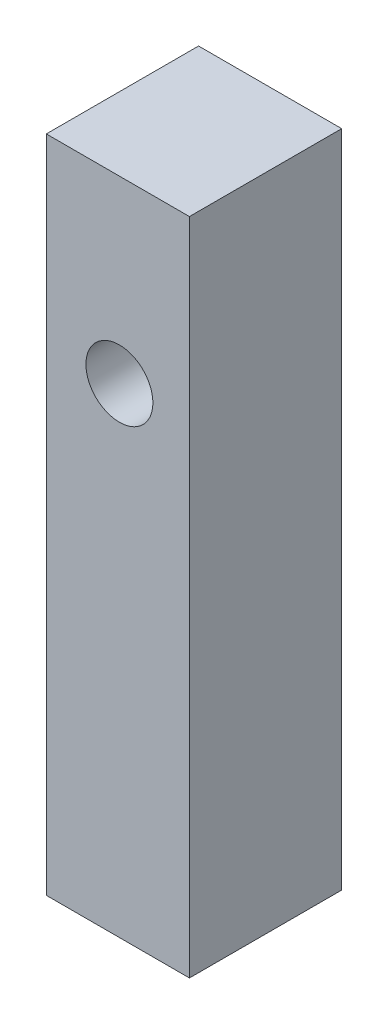
SolidWorks part; units mm, degrees
ref_plane "前视基准面" through (0, 0, 0) normal (0, 0, 1) x (1, 0, 0)
ref_plane "上视基准面" through (0, 0, 0) normal (0, 1, 0) x (1, 0, 0)
ref_plane "右视基准面" through (0, 0, 0) normal (1, 0, 0) x (0, 0, -1)
other "Configuration Table"
sketch "草图1" plane through (0, 0, 0) normal (0, 0, 1) x (1, 0, 0)
  line L5 (11.25, -15.755) -> (15.95, -15.755)
  line L6 (-23.0958, -15.755) -> (-18.4458, -15.755) construction
  line L7 (15.95, -5.9) -> (15.95, -0.65)
  line L8 (15.95, -0.65) -> (14.4099, -0.65)
  line L9 (14.4099, 0.65) -> (15.95, 0.65)
  line L10 (15.95, 0.65) -> (15.95, 5.9)
  line L11 (15.95, 5.9) -> (11.25, 5.9)
  line L12 (11.25, 5.9) -> (11.25, -5.9)
  line L13 (11.25, -5.9) -> (15.95, -5.9)
  line L14 (15.95, -15.755) -> (15.95, 0.65)
  line L17 (15.95, 0.65) -> (15.95, 5.9)
  line L18 (15.95, 5.9) -> (11.25, 5.9)
  line L19 (11.25, 5.9) -> (11.25, -15.755)
  circle A0 centre (13.65, 0) radius 1.1
  arc A1 (14.4099, 0.65) -> (14.4099, -0.65) centre (13.65, 0) ccw
  dimension "D2" = 2.2
  dimension "D1" = 0
extrude "凸台-拉伸1" add sketch "草图1" along normal blind 5
equation "\"2。2\"=3.0633"
